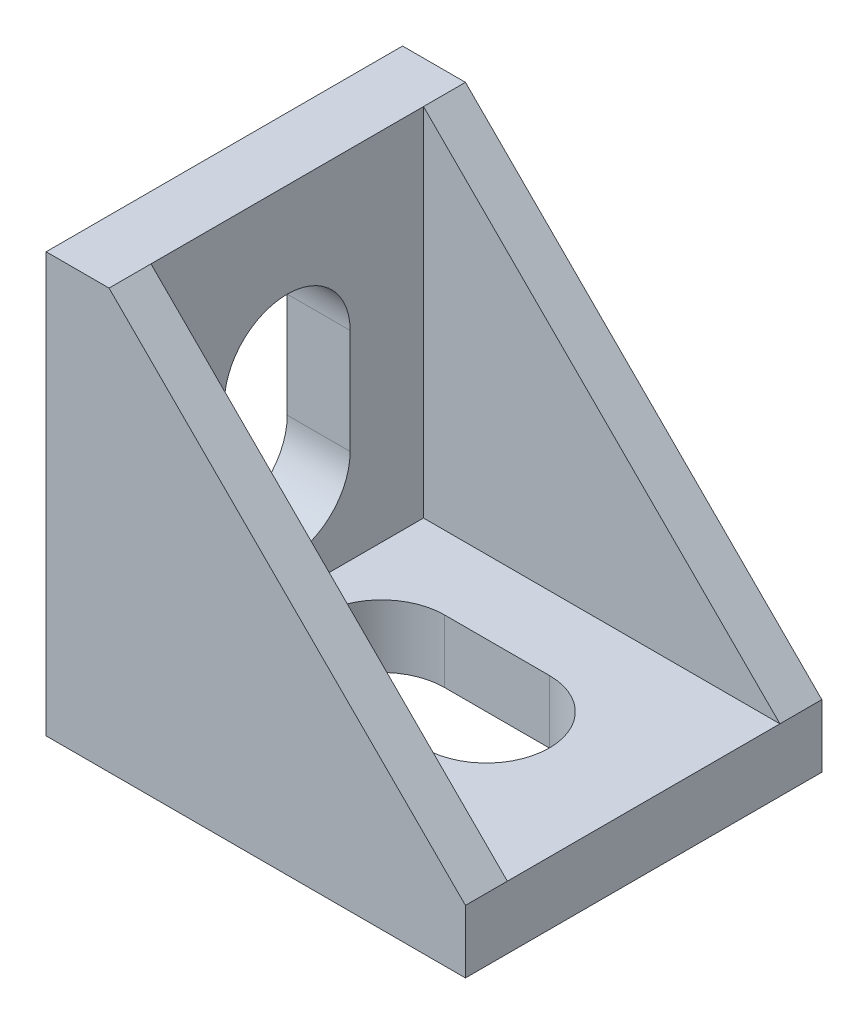
SolidWorks part; units mm, degrees
ref_plane "前视基准面" through (0, 0, 0) normal (0, 0, 1) x (1, 0, 0)
ref_plane "上视基准面" through (0, 0, 0) normal (0, 1, 0) x (1, 0, 0)
ref_plane "右视基准面" through (0, 0, 0) normal (1, 0, 0) x (0, 0, -1)
sketch "草图1" plane through (0, 0, 0) normal (0, 1, 0) x (1, 0, 0)
  line L0 (-2.1154, 1.2972) -> (2.8846, 1.2972) construction
  line L1 (-9.6154, 9.7972) -> (10.3846, 9.7972)
  line L2 (-9.6154, 9.7972) -> (-9.6154, -7.2028)
  line L3 (-9.6154, -7.2028) -> (10.3846, -7.2028)
  line L4 (10.3846, 9.7972) -> (10.3846, -7.2028)
  line L5 (-2.1154, 4.2972) -> (2.8846, 4.2972)
  line L6 (-2.1154, -1.7028) -> (2.8846, -1.7028)
  arc A0 (-2.1154, 4.2972) -> (-2.1154, -1.7028) centre (-2.1154, 1.2972) ccw
  arc A1 (2.8846, -1.7028) -> (2.8846, 4.2972) centre (2.8846, 1.2972) ccw
  point P6 (0.3846, 1.2972)
  point P11 (0.3846, 9.7972)
  point P12 (-9.6154, 1.2972)
  point P13 (0.3846, 9.7972)
  point P14 (0.3147, 1.1888)
  point P15 (0, 0)
  point P16 (0, 0)
  point P17 (0, 0)
  dimension "D1" = 20
  dimension "D2" = 17
  dimension "D3" = 6
  dimension "D4" = 5
extrude "凸台-拉伸1" add sketch "草图1" along normal blind 3
sketch "草图4" plane through (-9.6154, 0, 0) normal (-1, 0, 0) x (0, 0, 1)
  line L0 (-9.7972, 3) -> (7.2028, 3) construction
  line L1 (-9.7972, 0) -> (7.2028, 0)
  line L2 (-9.7972, 0) -> (-9.7972, 20)
  line L3 (-9.7972, 20) -> (7.2028, 20)
  line L4 (7.2028, 0) -> (7.2028, 20)
  dimension "D1" = 17
extrude "凸台-拉伸2" add sketch "草图4" against normal blind 3
sketch "草图5" plane through (-6.6154, 0, 0) normal (1, 0, 0) x (0, 0, -1)
  line L0 (1.2972, 12.5) -> (1.2972, 7.5) construction
  line L1 (4.2972, 12.5) -> (4.2972, 7.5)
  line L2 (-1.7028, 12.5) -> (-1.7028, 7.5)
  line L3 (-7.2028, 20) -> (9.7972, 20) construction
  line L4 (9.7972, 20) -> (9.7972, 3) construction
  arc A0 (4.2972, 12.5) -> (-1.7028, 12.5) centre (1.2972, 12.5) ccw
  arc A1 (-1.7028, 7.5) -> (4.2972, 7.5) centre (1.2972, 7.5) ccw
  point P2 (1.2972, 10)
  point P7 (1.2972, 20)
  point P8 (9.7972, 11.5)
  point P11 (0, 0)
  point P14 (0, 0)
  point P15 (0, 0)
  point P16 (0, 0)
  point P17 (0, 0)
  point P18 (0, 0)
  point P19 (0, 0)
  point P20 (0, 0)
  point P21 (0, 0)
  dimension "D1" = 6
  dimension "D2" = 5
  dimension "D3" = 10
sketch "草图6" plane through (0, 0, 7.2028) normal (0, 0, 1) x (1, 0, 0)
  line L0 (-6.6154, 20) -> (10.3846, 3)
  line L1 (10.3846, 3) -> (-6.6154, 3)
  line L2 (-6.6154, 3) -> (-6.6154, 20)
extrude "凸台-拉伸3" add sketch "草图6" against normal blind 2
sketch "草图7" plane through (0, 0, -9.7972) normal (0, 0, -1) x (-1, 0, 0)
  line L0 (6.6154, 20) -> (6.6154, 3)
  line L1 (6.6154, 3) -> (-10.3846, 3)
  line L2 (-10.3846, 3) -> (6.6154, 20)
extrude "凸台-拉伸4" add sketch "草图7" against normal blind 2
extrude "切除-拉伸2" cut sketch "草图5" against normal blind 12
sketch "草图9" plane through (-9.6154, 0, 0) normal (-1, 0, 0) x (0, 0, 1)
  line L0 (-1.2972, 20) -> (-1.2972, 0) construction
  line L1 (7.2028, 20) -> (-9.7972, 20) construction
  line L2 (-9.7972, 0) -> (7.2028, 0) construction
  line L3 (-1.2972, 20) -> (-1.2972, 15.5) construction
  line L4 (-1.2972, 4.5) -> (-1.2972, 0) construction
  line L5 (-2.1972, 17.75) -> (-0.3972, 17.75) construction
  line L8 (-2.1972, 18.65) -> (-0.3972, 18.65)
  line L9 (-2.1972, 16.85) -> (-0.3972, 16.85)
  line L10 (-2.1972, 2.25) -> (-0.3972, 2.25) construction
  line L11 (-2.1972, 3.15) -> (-0.3972, 3.15)
  line L12 (-2.1972, 1.35) -> (-0.3972, 1.35)
  arc A0 (1.7028, 12.5) -> (-4.2972, 12.5) centre (-1.2972, 12.5) ccw construction
  arc A1 (-4.2972, 7.5) -> (1.7028, 7.5) centre (-1.2972, 7.5) ccw construction
  arc A4 (-2.1972, 18.65) -> (-2.1972, 16.85) centre (-2.1972, 17.75) ccw
  arc A5 (-0.3972, 16.85) -> (-0.3972, 18.65) centre (-0.3972, 17.75) ccw
  arc A6 (-2.1972, 3.15) -> (-2.1972, 1.35) centre (-2.1972, 2.25) ccw
  arc A7 (-0.3972, 1.35) -> (-0.3972, 3.15) centre (-0.3972, 2.25) ccw
  point P6 (-1.2972, 15.5)
  point P7 (-1.2972, 4.5)
  point P11 (-1.2972, 17.75)
  point P19 (-1.2972, 17.75)
  point P24 (0.5028, 17.75)
  point P25 (-3.0972, 17.75)
  point P26 (-1.2972, 2.25)
  point P29 (-1.2972, 2.25)
  point P34 (-3.0972, 2.25)
  point P35 (0.5028, 2.25)
  point P36 (0, 0)
  point P37 (0, 0)
  dimension "D1" = 1.8
  dimension "D2" = 3.6
  dimension "D3" = 1.8
  dimension "D4" = 3.6
extrude "凸台-拉伸6" add sketch "草图9" along normal blind 1
sketch "草图10" plane through (0, 0, 0) normal (0, -1, 0) x (1, 0, 0)
  line L0 (-9.6154, -1.2972) -> (10.3846, -1.2972) construction
  line L1 (-9.6154, -9.7972) -> (-9.6154, 7.2028) construction
  line L2 (10.3846, 7.2028) -> (10.3846, -9.7972) construction
  line L3 (-9.6154, -1.2972) -> (-5.1154, -1.2972) construction
  line L4 (5.8846, -1.2972) -> (10.3846, -1.2972) construction
  line L5 (-7.3654, -0.3972) -> (-7.3654, -2.1972) construction
  line L6 (-6.4654, -0.3972) -> (-6.4654, -2.1972)
  line L7 (-8.2654, -0.3972) -> (-8.2654, -2.1972)
  line L8 (8.1346, -0.3972) -> (8.1346, -2.1972) construction
  line L9 (9.0346, -0.3972) -> (9.0346, -2.1972)
  line L10 (7.2346, -0.3972) -> (7.2346, -2.1972)
  arc A0 (-2.1154, 1.7028) -> (-2.1154, -4.2972) centre (-2.1154, -1.2972) ccw construction
  arc A1 (2.8846, -4.2972) -> (2.8846, 1.7028) centre (2.8846, -1.2972) ccw construction
  arc A2 (-6.4654, -0.3972) -> (-8.2654, -0.3972) centre (-7.3654, -0.3972) ccw
  arc A3 (-8.2654, -2.1972) -> (-6.4654, -2.1972) centre (-7.3654, -2.1972) ccw
  arc A4 (9.0346, -0.3972) -> (7.2346, -0.3972) centre (8.1346, -0.3972) ccw
  arc A5 (7.2346, -2.1972) -> (9.0346, -2.1972) centre (8.1346, -2.1972) ccw
  point P6 (-5.1154, -1.2972)
  point P7 (5.8846, -1.2972)
  point P16 (-7.3654, -1.2972)
  point P17 (8.1346, -1.2972)
  point P20 (-7.3654, -1.2972)
  point P25 (8.1346, -1.2972)
  point P32 (-7.3654, 0.5028)
  point P33 (-7.3654, -3.0972)
  point P34 (8.1346, 0.5028)
  point P35 (8.1346, -3.0972)
  point P36 (-7.3654, -1.2972)
  point P37 (0, 0)
  point P38 (0, 0)
  dimension "D1" = 1.8
  dimension "D2" = 3.6
  dimension "D3" = 1.8
  dimension "D4" = 3.6
extrude "凸台-拉伸7" add sketch "草图10" along normal blind 1
